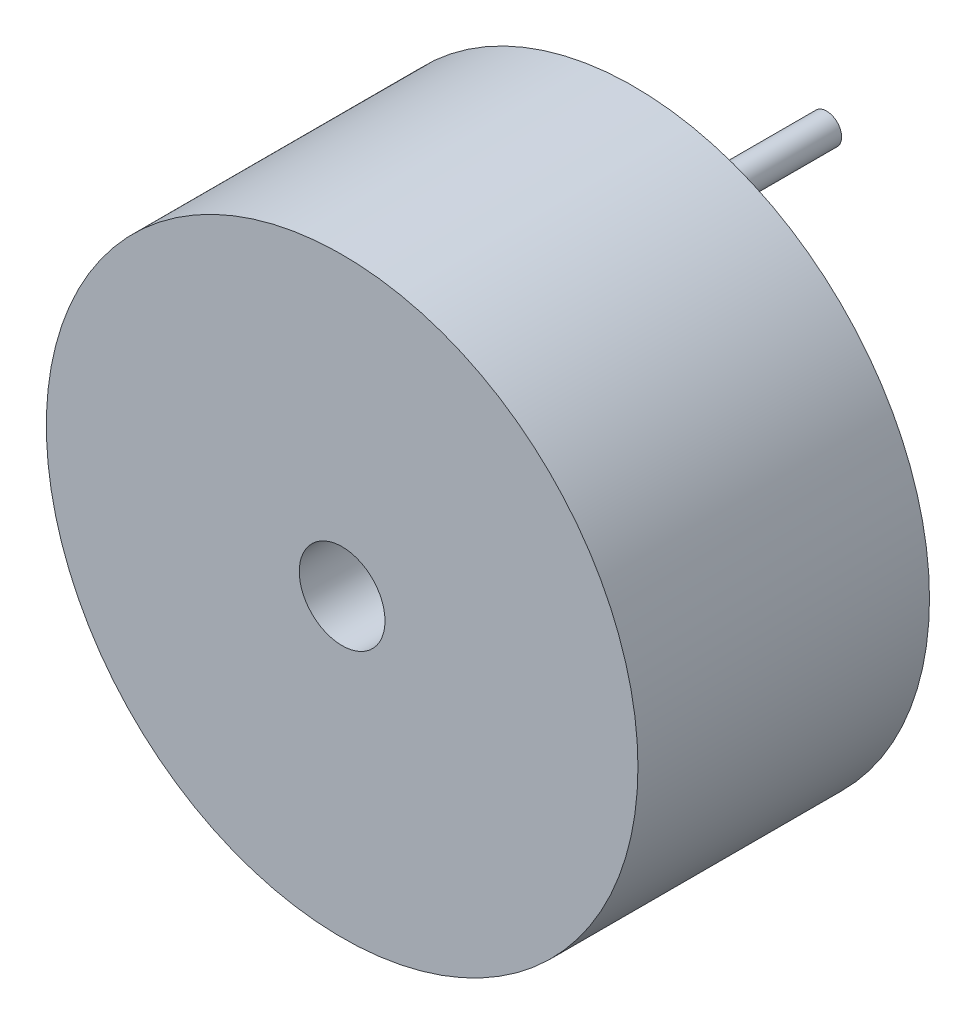
SolidWorks part; units mm, degrees
ref_plane "Front Plane" through (0, 0, 0) normal (0, 0, 1) x (1, 0, 0)
ref_plane "Top Plane" through (0, 0, 0) normal (0, 1, 0) x (1, 0, 0)
ref_plane "Right Plane" through (0, 0, 0) normal (1, 0, 0) x (0, 0, -1)
sketch "Sketch1" plane through (0, 0, 0) normal (0, 0, 1) x (1, 0, 0)
  circle A0 centre (0, 0) radius 6.9
  dimension "D1" = 13.8
extrude "Boss-Extrude1" add sketch "Sketch1" along normal blind 6.8
sketch "Sketch2" plane through (0, 0, 6.8) normal (0, 0, 1) x (1, 0, 0)
  circle A0 centre (0, 0) radius 1
  dimension "D1" = 2
extrude "Cut-Extrude1" cut sketch "Sketch2" against normal blind 2
sketch "Sketch3" plane through (0, 0, 0) normal (0, 0, -1) x (-1, 0, 0)
  line L1 (0, -3.8) -> (0, 3.8) construction
  circle A2 centre (0, 3.8) radius 0.35
  circle A3 centre (0, -3.8) radius 0.35
  dimension "D3" = 0.7
  dimension "D4" = 7.6
extrude "Boss-Extrude2" add sketch "Sketch3" along normal blind 4.5
